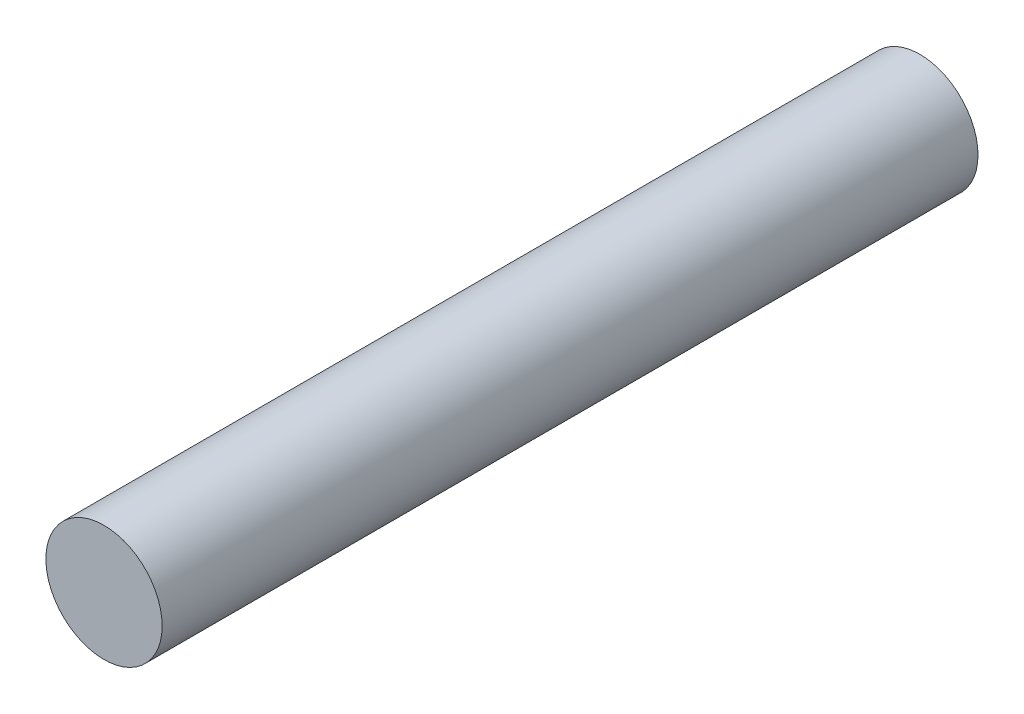
SolidWorks part; units mm, degrees
ref_plane "前视基准面" through (0, 0, 0) normal (0, 0, 1) x (1, 0, 0)
ref_plane "上视基准面" through (0, 0, 0) normal (0, 1, 0) x (1, 0, 0)
ref_plane "右视基准面" through (0, 0, 0) normal (1, 0, 0) x (0, 0, -1)
sketch "草图1" plane through (0, 0, 0) normal (0, 0, 1) x (1, 0, 0)
  circle A0 centre (0, 0) radius 2.85
  dimension "D1" = 5.7
extrude "凸台-拉伸1" add sketch "草图1" along normal blind 40
